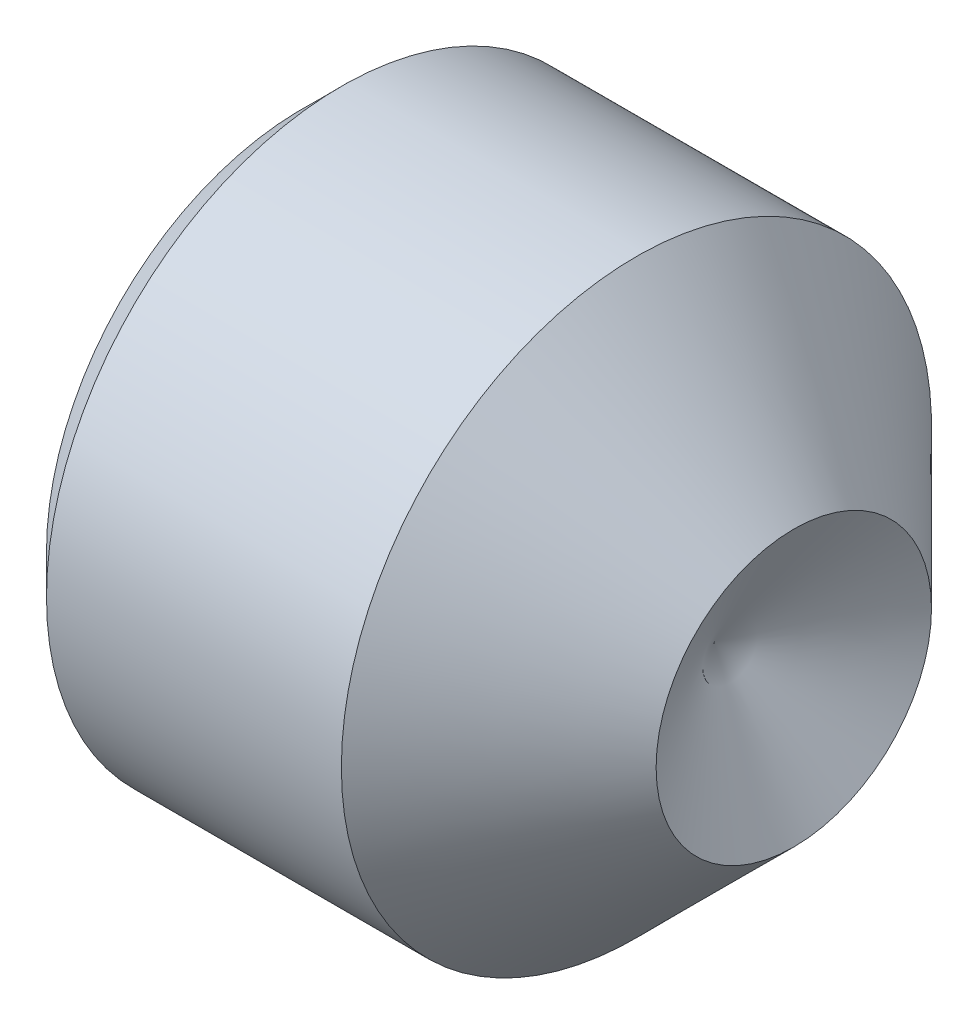
SolidWorks part; units mm, degrees
revolve "基体-旋转" add sketch "草图2" angle 360 about L6
sketch "草图2" plane through (0, 0, 0) normal (0, 0, 1) x (1, 0, 0)
  line L0 (0, 0) -> (2.5, 0)
  line L1 (2.5, 0) -> (2.5, 0.7)
  line L2 (2.5, 0.7) -> (1.7, 1.5)
  line L3 (1.7, 1.5) -> (0.201, 1.5)
  line L4 (0.201, 1.5) -> (0, 1.299)
  line L5 (0, 1.299) -> (0, 0)
  line L6 (-0.2621, 0) -> (5.2308, 0) construction
  dimension "l" = 2.5
  dimension "df" = 2.598
  dimension "d" = 3
  dimension "dz" = 1.4
  dimension "D1" = 45
  dimension "D2" = 45
cosmetic thread "装饰螺纹线1" parameters "D1"=1.7, "df"=2.598
revolve "切除-旋转2" cut sketch "草图6" angle 360 about L0
sketch "草图6" plane through (0, 0, 0) normal (0, 0, 1) x (1, 0, 0)
  line L0 (-1.7277, 0) -> (5.9194, 0) construction
  line L1 (-0.2621, 0) -> (5.2308, 0) construction
  line L2 (2.5, 0) -> (2.5, 0.7)
  line L3 (2.5, -0.7) -> (2.5, 0.7) construction
  line L4 (2.5, 0.7) -> (2.0959, 0)
  line L5 (2.0959, 0) -> (2.5, 0)
  line L8 (2.5, 0.7) -> (1.7, 1.5) construction
  dimension "D1" = 60
material "45H级"
ref_plane "前视" through (0, 0, 0) normal (0, 0, 1) x (1, 0, 0)
ref_plane "上视" through (0, 0, 0) normal (0, 1, 0) x (1, 0, 0)
ref_plane "右视" through (0, 0, 0) normal (1, 0, 0) x (0, 0, -1)
sketch "尺寸草图" plane through (0, 0, 0) normal (0, 0, 1) x (1, 0, 0)
  line L0 (0, 0) -> (2.5, 0)
  point P3 (1.2, 0)
  point P4 (2, 0)
  point P5 (2.598, 0)
  point P6 (1.1, 0)
  point P7 (0.77, 0)
  point P8 (3, 0)
  dimension "l" = 2.5
  dimension "df" = 2.598
  dimension "d" = 3
  dimension "dz" = 1.4
  dimension "t" = 1.2
  dimension "P" = 0.5
  dimension "e" = 1.73
sketch "草图3" plane through (0, 0, 0) normal (-1, 0, 0) x (0, 0, 1)
  line L1 (0.865, 0) -> (0.4325, 0.7491)
  line L2 (0.4325, 0.7491) -> (-0.4325, 0.7491)
  line L3 (-0.4325, 0.7491) -> (-0.865, 0)
  line L4 (-0.865, 0) -> (-0.4325, -0.7491)
  line L5 (-0.4325, -0.7491) -> (0.4325, -0.7491)
  line L6 (0.4325, -0.7491) -> (0.865, 0)
  circle A0 centre (0, 0) radius 0.7491 construction
  dimension "e" = 1.73
extrude "切除-拉伸1" cut sketch "草图3" against normal blind 1.2
sketch "草图4" plane through (0, 0, 0) normal (0, 0, 1) x (1, 0, 0)
  line L0 (-0.1213, 0) -> (1.428, 0) construction
  line L1 (-0.2621, 0) -> (5.2308, 0) construction
  line L2 (1.2, 0.7491) -> (1.6325, 0)
  line L3 (1.6325, 0) -> (1.2, 0)
  line L4 (1.2, 0) -> (1.2, 0.7491)
  dimension "D1" = 60
revolve "切除-旋转1" cut sketch "草图4" angle 360 about L0
sketch "草图7" plane through (0, 0, 0) normal (0, 0, 1) x (1, 0, 0)
  line L0 (0.201, 1.5) -> (0.701, 1.5)
  line L1 (0.701, 1.5) -> (0.4483, 1.067)
  line L2 (0.4483, 1.067) -> (0.201, 1.5)
  line L4 (1.7, 1.5) -> (0.201, 1.5) construction
  line L5 (0.201, 1.5) -> (0.201, -1.5) construction
  line L6 (-0.1682, 0) -> (3.525, 0) construction
  line L7 (-0.2621, 0) -> (5.2308, 0) construction
  dimension "D1" = 0.5
  dimension "D2" = 0.433
  dimension "D3" = 60
revolve "切除-旋转3" [suppressed] cut sketch "草图7" angle 360 about L6
pattern_linear "阵列(线性)1" [suppressed] count 3 spacing 0.5
equation "\"l@草图2\"=\"l@尺寸草图\""
equation "\"d@草图2\" = \"d@尺寸草图\""
equation "\"df@草图2\" = \"df@尺寸草图\""
equation "\"dz@草图2\" = \"dz@尺寸草图\""
equation "\"e@草图3\" = \"e@尺寸草图\""
equation "\"t@切除-拉伸1\"=\"t@尺寸草图\""
equation "\"df@装饰螺纹线1\"=\"df@尺寸草图\""
equation "\"D1@草图7\"=\"P@尺寸草图\""
equation "\"D2@草图7\" = \"D1@草图7\"*0.866"
equation "\"D3@阵列(线性)1\" = \"P@尺寸草图\""
equation "\"D1@阵列(线性)1\" = (\"l@尺寸草图\"-\"d@尺寸草图\"/2+\"dz@尺寸草图\"/2)/\"P@尺寸草图\""
equation "\"D1@装饰螺纹线1\"=\"l@尺寸草图\"-\"d@尺寸草图\"/2+\"dz@尺寸草图\"/2"
